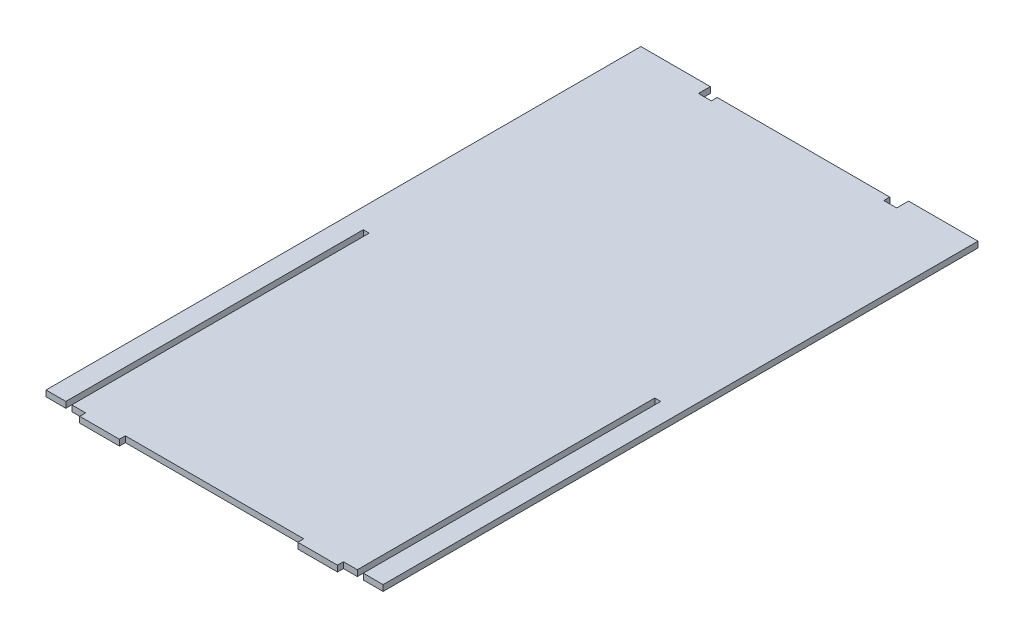
SolidWorks part; units mm, degrees
ref_plane "Front Plane" through (0, 0, 0) normal (0, 0, 1) x (1, 0, 0)
ref_plane "Top Plane" through (0, 0, 0) normal (0, 1, 0) x (1, 0, 0)
ref_plane "Right Plane" through (0, 0, 0) normal (1, 0, 0) x (0, 0, -1)
sketch "Sketch1" plane through (0, 0, 0) normal (0, 1, 0) x (1, 0, 0)
  line L0 (300, 0) -> (300, -6)
  line L2 (0, 0) -> (0, 600)
  line L3 (0, 600) -> (340, 600)
  line L4 (340, 0) -> (340, 600)
  line L5 (300, -6) -> (260, -6)
  line L6 (260, -6) -> (260, 0)
  line L7 (40, 0) -> (40, -6)
  line L8 (40, -6) -> (80, -6)
  line L9 (80, -6) -> (80, 0)
  line L10 (40, 0) -> (0, 0)
  line L11 (80, 0) -> (260, 0)
  line L12 (300, 0) -> (340, 0)
  point P11 (80, -3)
  dimension "D1" = 340
  dimension "D2" = 600
  dimension "D3" = 40
  dimension "D4" = 6
  dimension "D5" = 40
  dimension "D6" = 180
extrude "Boss-Extrude1" add sketch "Sketch1" along normal blind 6
sketch "Sketch2" plane through (0, 6, 0) normal (0, 1, 0) x (1, 0, 0)
  line L1 (20, 0) -> (26, 0)
  line L2 (20, 0) -> (20, 300)
  line L3 (20, 300) -> (26, 300)
  line L4 (26, 0) -> (26, 300)
  line L5 (0, 600) -> (0, 0) construction
  line L6 (0, 0) -> (40, 0) construction
  line L7 (0, 0) -> (40, 0) construction
  dimension "D1" = 300
  dimension "D2" = 6
  dimension "D3" = 20
extrude "Cut-Extrude1" cut sketch "Sketch2" against normal blind 6
pattern_linear "LPattern1" count 2 spacing 294 along (1, 0, 0) of "Cut-Extrude1"
sketch "Sketch3" plane through (0, 6, 0) normal (0, 1, 0) x (1, 0, 0)
  line L3 (340, 600) -> (0, 600) construction
  line L4 (70, 600) -> (270, 600)
  line L18 (70, 600) -> (70, 588)
  line L19 (70, 588) -> (83, 588)
  line L20 (83, 588) -> (83, 594)
  line L21 (270, 600) -> (270, 588)
  line L22 (270, 588) -> (257, 588)
  line L23 (257, 588) -> (257, 594)
  line L24 (83, 594) -> (257, 594)
  line L25 (0, 600) -> (0, 0) construction
  dimension "D1" = 200
  dimension "D2" = 12
  dimension "D3" = 13
  dimension "D4" = 6
  dimension "D5" = 70
extrude "Cut-Extrude2" cut sketch "Sketch3" against normal blind 6
